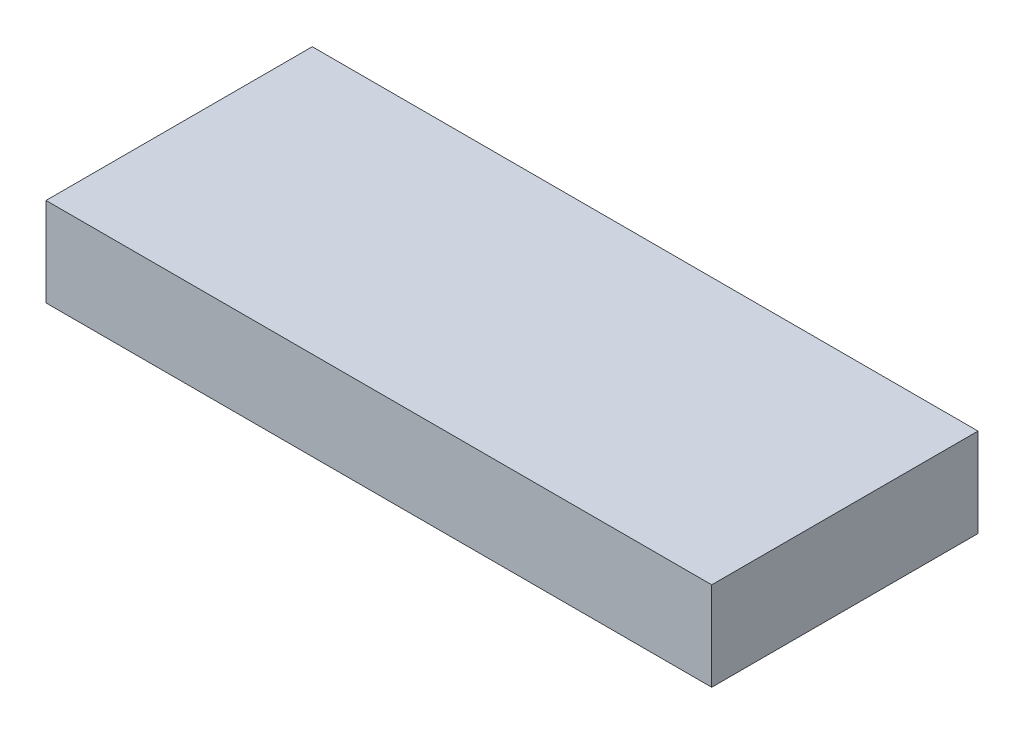
SolidWorks part; units mm, degrees
ref_plane "Plan de face" through (0, 0, 0) normal (0, 0, 1) x (1, 0, 0)
ref_plane "Plan de dessus" through (0, 0, 0) normal (0, 1, 0) x (1, 0, 0)
ref_plane "Plan de droite" through (0, 0, 0) normal (1, 0, 0) x (0, 0, -1)
sketch "Esquisse1" plane through (0, 0, 0) normal (0, 0, 1) x (1, 0, 0)
  line L1 (-7.5, -1) -> (7.5, -1)
  line L2 (-7.5, -1) -> (-7.5, 1)
  line L3 (-7.5, 1) -> (7.5, 1)
  line L4 (7.5, -1) -> (7.5, 1)
  line L5 (-7.5, -1) -> (7.5, 1) construction
  line L6 (-7.5, 1) -> (7.5, -1) construction
  point P0 (0, 0)
  dimension "D1" = 15
  dimension "D2" = 2
extrude "Boss.-Extru.1" add sketch "Esquisse1" along normal blind 6
